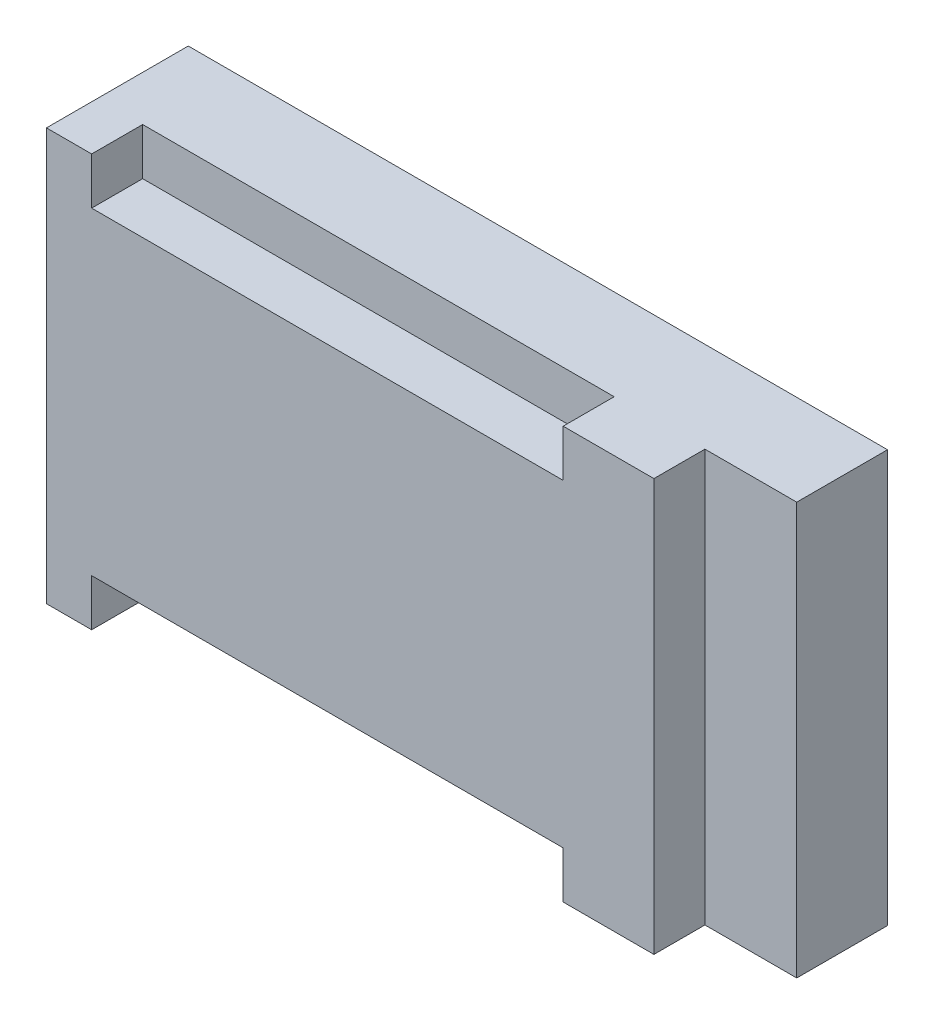
SolidWorks part; units mm, degrees
ref_plane "Płaszczyzna przednia" through (0, 0, 0) normal (0, 0, 1) x (1, 0, 0)
ref_plane "Płaszczyzna górna" through (0, 0, 0) normal (0, 1, 0) x (1, 0, 0)
ref_plane "Płaszczyzna prawa" through (0, 0, 0) normal (1, 0, 0) x (0, 0, -1)
sketch "Szkic1" plane through (0, 0, 0) normal (0, 0, 1) x (1, 0, 0)
  line L1 (-76.0303, 33.4271) -> (61.0697, 33.4271)
  line L2 (-76.0303, 33.4271) -> (-76.0303, -47.3729)
  line L3 (-76.0303, -47.3729) -> (61.0697, -47.3729)
  line L4 (61.0697, 33.4271) -> (61.0697, -47.3729)
  dimension "D1" = 137.1
  dimension "D2" = 80.8
extrude "Dodanie-wyciągnięcie1" add sketch "Szkic1" along normal blind 27.8
sketch "Szkic2" plane through (0, 0, 27.8) normal (0, 0, 1) x (1, 0, 0)
  line L0 (-76.0303, -47.3729) -> (61.0697, -47.3729) construction
  line L1 (-67.1714, -47.3729) -> (25.2736, -47.3729)
  line L2 (-67.1714, -47.3729) -> (-67.1714, -38.1729)
  line L3 (-67.1714, -38.1729) -> (25.2736, -38.1729)
  line L4 (25.2736, -47.3729) -> (25.2736, -38.1729)
  line L5 (-67.1714, -38.1729) -> (-67.1714, 45.3857) construction
  line L6 (25.2736, -38.1729) -> (25.2736, 48.8737) construction
  line L7 (61.0697, 33.4271) -> (-76.0303, 33.4271) construction
  line L8 (-67.1714, 33.4271) -> (25.2736, 33.4271)
  line L9 (-67.1714, 33.4271) -> (-67.1714, 24.2271)
  line L10 (-67.1714, 24.2271) -> (25.2736, 24.2271)
  line L11 (25.2736, 33.4271) -> (25.2736, 24.2271)
  line L13 (61.0697, 33.4271) -> (43.0687, 33.4271)
  line L14 (61.0697, 33.4271) -> (61.0697, -47.3729)
  line L15 (61.0697, -47.3729) -> (43.0687, -47.3729)
  line L16 (43.0687, 33.4271) -> (43.0687, -47.3729)
  dimension "D1" = 9.2
  dimension "D2" = 9.2
extrude "Wytnij-wyciągnięcie1" cut sketch "Szkic2" against normal blind 10
sketch "Szkic3" plane through (0, 0, 0) normal (0, 0, -1) x (-1, 0, 0)
  line L0 (76.0303, -6.9729) -> (-61.0697, -6.9729) construction
  line L1 (76.0303, 33.4271) -> (76.0303, -47.3729) construction
  line L2 (-61.0697, -47.3729) -> (-61.0697, 33.4271) construction
  line L3 (66.8303, 33.4271) -> (66.8303, -47.3729) construction
  line L4 (-61.0697, 33.4271) -> (76.0303, 33.4271) construction
  line L5 (76.0303, -47.3729) -> (-61.0697, -47.3729) construction
  line L6 (65.5803, 33.4271) -> (65.5803, -47.3729) construction
  line L7 (-35.8197, 33.4271) -> (-35.8197, -61.2612) construction
  line L8 (65.5803, -26.7229) -> (-35.8197, -26.7229) construction
  line L9 (65.5803, 12.7771) -> (-35.8197, 12.7771) construction
  line L10 (65.5803, -27.9729) -> (-35.8197, -27.9729) construction
  line L11 (65.5803, 14.0271) -> (-35.8197, 14.0271) construction
  circle A1 centre (65.5803, 12.7771) radius 1.25
  circle A2 centre (65.5803, -26.7229) radius 1.25
  circle A3 centre (-35.8197, -26.7229) radius 1.25
  circle A4 centre (-35.8197, 14.0271) radius 1.25
  dimension "D1" = 9.2
  dimension "D2" = 1.25
  dimension "D3" = 101.4
extrude "Wytnij-wyciągnięcie2" cut sketch "Szkic3" against normal blind 5
